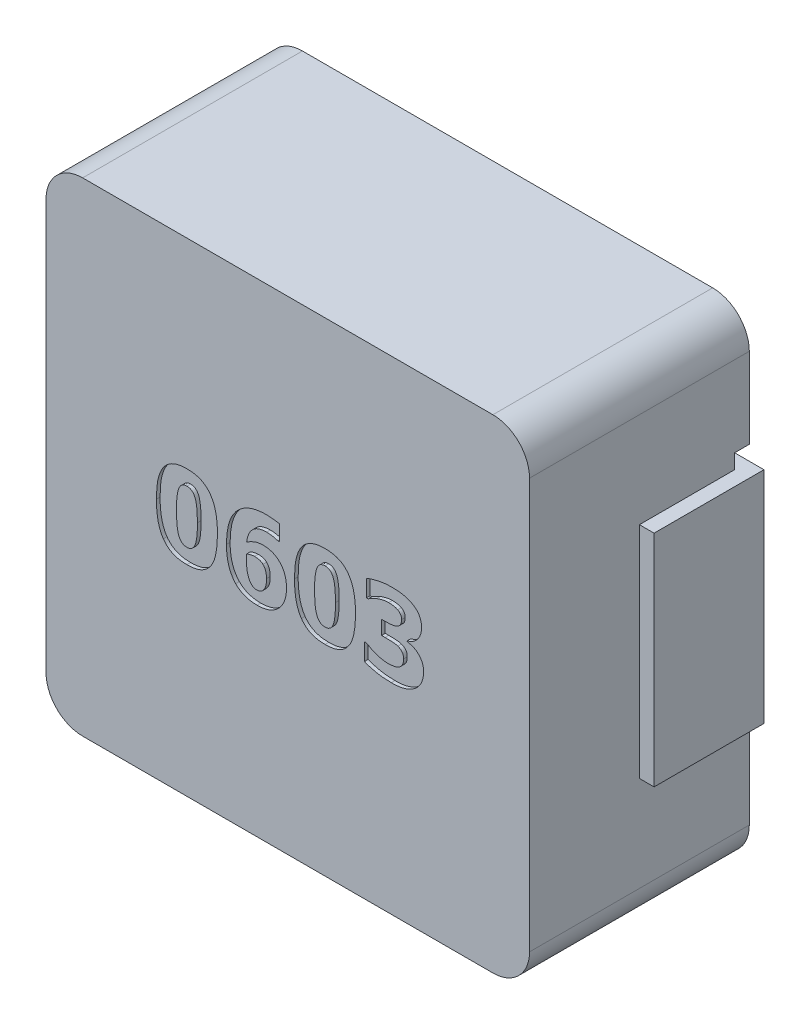
SolidWorks part; units mm, degrees
ref_plane "前视基准面" through (0, 0, 0) normal (0, 0, 1) x (1, 0, 0)
ref_plane "上视基准面" through (0, 0, 0) normal (0, 1, 0) x (1, 0, 0)
ref_plane "右视基准面" through (0, 0, 0) normal (1, 0, 0) x (0, 0, -1)
sketch "草图1" plane through (0, 0, 0) normal (0, 0, 1) x (1, 0, 0)
  line L1 (-2.8, 3.3) -> (2.8, 3.3)
  line L2 (-3.3, 2.8) -> (-3.3, -2.8)
  line L3 (-2.8, -3.3) -> (2.8, -3.3)
  line L4 (3.3, 2.8) -> (3.3, -2.8)
  line L5 (-3.3, 3.3) -> (3.3, -3.3) construction
  line L6 (-3.3, -3.3) -> (3.3, 3.3) construction
  arc A0 (2.8, -3.3) -> (3.3, -2.8) centre (2.8, -2.8) ccw
  arc A1 (-3.3, -2.8) -> (-2.8, -3.3) centre (-2.8, -2.8) ccw
  arc A2 (-2.8, 3.3) -> (-3.3, 2.8) centre (-2.8, 2.8) ccw
  arc A3 (2.8, 3.3) -> (3.3, 2.8) centre (2.8, 2.8) cw
  point P0 (0, 0)
  dimension "D3" = 0.5
  dimension "D1" = 6.6
  dimension "D2" = 6.6
extrude "凸台-拉伸1" add sketch "草图1" along normal blind 3
sketch "草图2" plane through (0, 0, 0) normal (0, 0, -1) x (-1, 0, 0)
  line L0 (3.3, 2.8) -> (3.3, -2.8) construction
  line L1 (3.3, -1.7) -> (1.85, -1.7)
  line L2 (3.3, -1.7) -> (3.3, 1.7)
  line L3 (3.3, 1.7) -> (1.85, 1.7)
  line L4 (1.85, -1.7) -> (1.85, 1.7)
  line L5 (0, 0) -> (3.3, 0) construction
  line L6 (0, 0) -> (0, -3.3) construction
  line L7 (2.8, -3.3) -> (-2.8, -3.3) construction
  line L8 (-3.3, -1.7) -> (-3.3, 1.7)
  line L9 (-3.3, 1.7) -> (-1.85, 1.7)
  line L10 (-1.85, -1.7) -> (-1.85, 1.7)
  line L11 (-3.3, -1.7) -> (-1.85, -1.7)
  dimension "D1" = 1.45
  dimension "D2" = 3.4
extrude "切除-拉伸1" cut sketch "草图2" against normal blind 0.2
sketch "草图3" plane through (0, 0, 0) normal (0, 0, -1) x (-1, 0, 0)
  line L0 (0, 0) -> (7.5225, 0) construction
  line L1 (3.3, -1.7) -> (3.3, 1.7) construction
  line L2 (3.5, 1.5) -> (2.1, 1.5)
  line L3 (3.5, 1.5) -> (3.5, -1.5)
  line L4 (3.5, -1.5) -> (2.1, -1.5)
  line L5 (2.1, 1.5) -> (2.1, -1.5)
  line L6 (3.5, 1.5) -> (2.1, -1.5) construction
  line L7 (3.5, -1.5) -> (2.1, 1.5) construction
  line L8 (0, 0) -> (0, -3.3) construction
  line L9 (2.8, -3.3) -> (-2.8, -3.3) construction
  line L10 (-3.5, 1.5) -> (-2.1, 1.5)
  line L11 (-3.5, 1.5) -> (-3.5, -1.5)
  line L12 (-3.5, -1.5) -> (-2.1, -1.5)
  line L13 (-2.1, 1.5) -> (-2.1, -1.5)
  point P3 (2.8, 0)
  dimension "D1" = 1.4
  dimension "D2" = 3
  dimension "D3" = 0.2
extrude "凸台-拉伸2" add sketch "草图3" against normal blind 1.5
sketch "草图4" plane through (0, 0, 3) normal (0, 0, 1) x (1, 0, 0)
  text T0 "0603" font "Tahoma" height in points 4
  point P1 (0, 0)
  point P2 (0, 0)
  point P3 (0, 0)
  point P4 (0, 0)
extrude "切除-拉伸2" cut sketch "草图4" against normal blind 0.05
